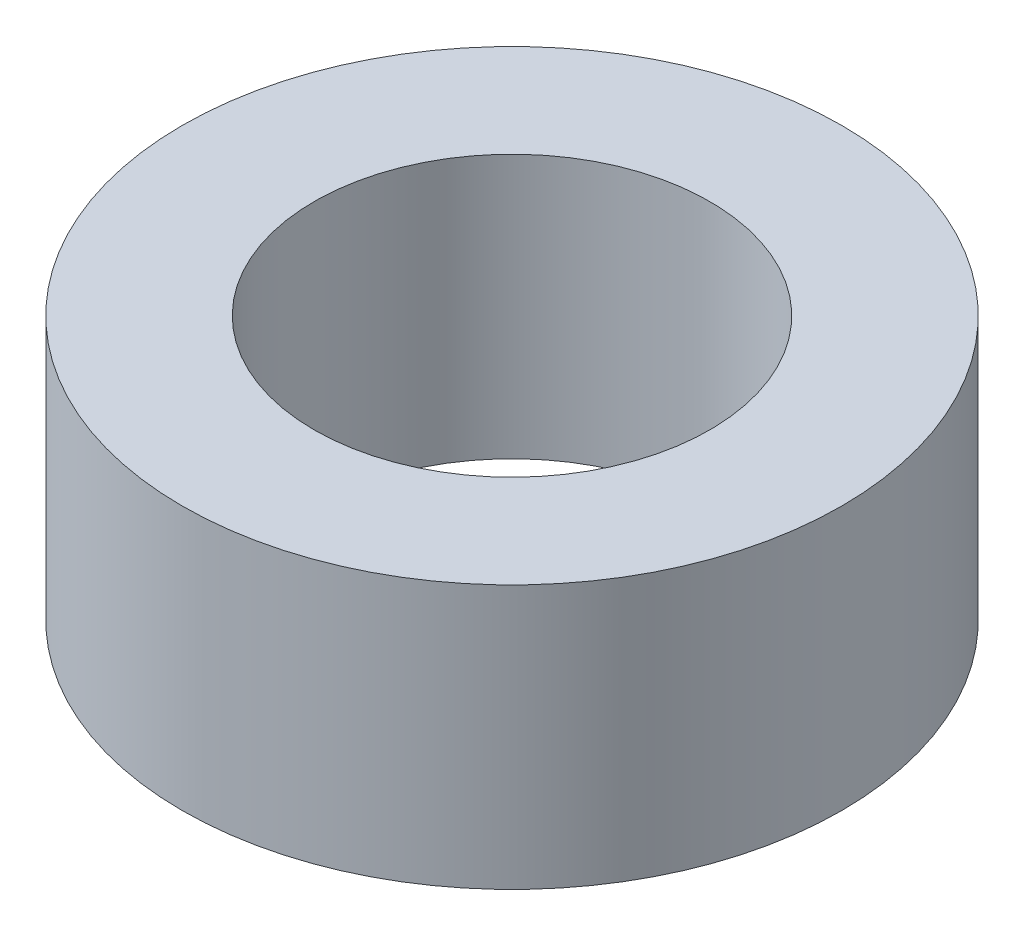
SolidWorks part; units mm, degrees
ref_plane "Спереди" through (0, 0, 0) normal (0, 0, 1) x (1, 0, 0)
ref_plane "Сверху" through (0, 0, 0) normal (0, 1, 0) x (1, 0, 0)
ref_plane "Справа" through (0, 0, 0) normal (1, 0, 0) x (0, 0, -1)
sketch "Эскиз1" plane through (0, 0, 0) normal (0, 1, 0) x (1, 0, 0)
  circle A0 centre (0, 0) radius 1.5
  circle A1 centre (0, 0) radius 2.5
extrude "Бобышка-Вытянуть1" add sketch "Эскиз1" along normal blind 2
